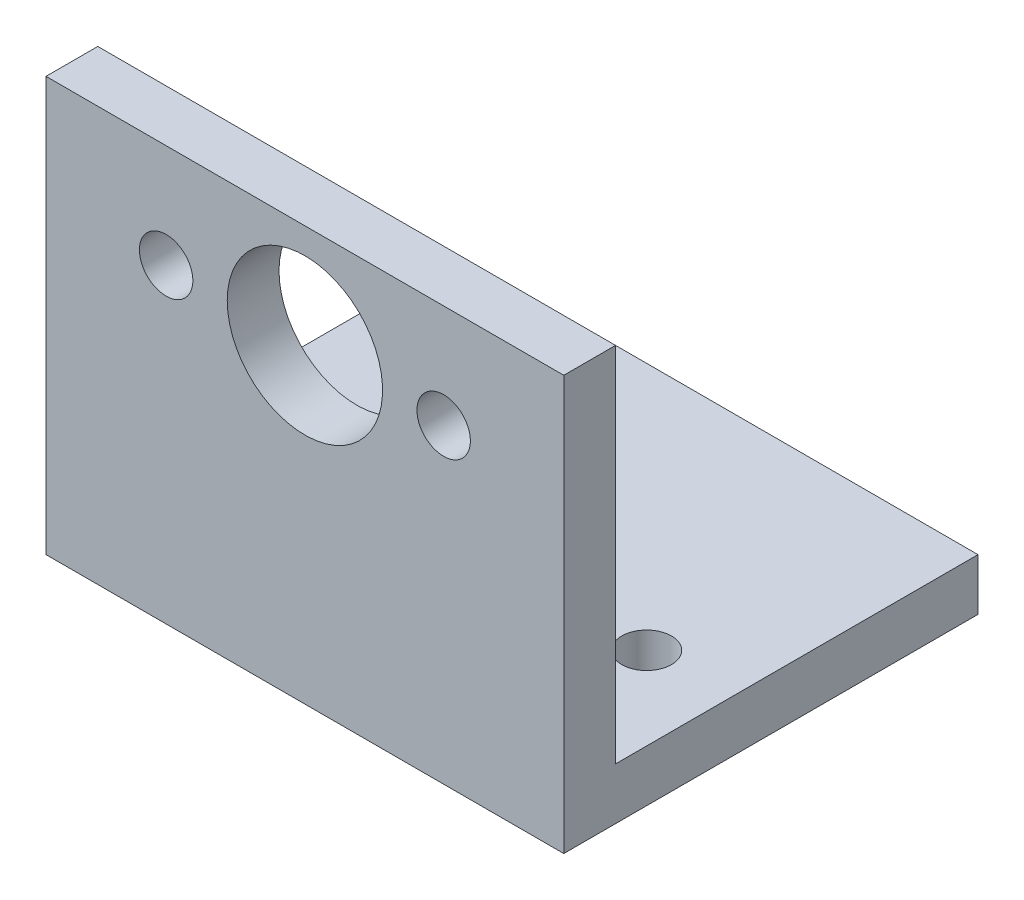
SolidWorks part; units mm, degrees
ref_plane "Front Plane" through (0, 0, 0) normal (0, 0, 1) x (1, 0, 0)
ref_plane "Top Plane" through (0, 0, 0) normal (0, 1, 0) x (1, 0, 0)
ref_plane "Right Plane" through (0, 0, 0) normal (1, 0, 0) x (0, 0, -1)
sketch "Sketch2" plane through (0, 0, 0) normal (1, 0, 0) x (0, 0, -1)
  line L0 (0, 0) -> (25.4, 0)
  line L1 (25.4, 0) -> (25.4, 3.175)
  line L2 (25.4, 3.175) -> (3.175, 3.175)
  line L3 (3.175, 3.175) -> (3.175, 25.4)
  line L4 (3.175, 25.4) -> (0, 25.4)
  line L5 (0, 25.4) -> (0, 0)
  dimension "D1" = 3.175
  dimension "D2" = 3.175
  dimension "D3" = 25.4
  dimension "D4" = 25.4
extrude "Boss-Extrude1" add sketch "Sketch2" along normal blind 31.75
sketch "Sketch3" plane through (0, 0, -3.175) normal (0, 0, -1) x (-1, 0, 0)
  line L1 (0, 3.175) -> (0, 25.4) construction
  line L2 (-31.75, 0) -> (0, 0) construction
  circle A0 centre (-15.875, 19.05) radius 4.7625
  circle A1 centre (-7.366, 19.05) radius 1.6383
  circle A2 centre (-24.384, 19.05) radius 1.6383
  dimension "D1" = 8.509
  dimension "D2" = 8.509
  dimension "D3" = 3.2766
  dimension "D4" = 3.2766
  dimension "D6" = 9.525
  dimension "D5" = 19.05
  dimension "D7" = 15.875
extrude "Cut-Extrude1" cut sketch "Sketch3" against normal through all
sketch "Sketch4" plane through (0, 3.175, 0) normal (0, 1, 0) x (1, 0, 0)
  line L0 (0, 25.4) -> (0, 3.175) construction
  line L1 (31.75, 25.4) -> (31.75, 3.175) construction
  line L2 (31.75, 25.4) -> (0, 25.4) construction
  circle A1 centre (5.08, 21.59) radius 1.524
  circle A2 centre (26.67, 10.16) radius 1.524
  dimension "D1" = 5.08
  dimension "D3" = 5.08
  dimension "D5" = 3.81
  dimension "D6" = 15.24
extrude "Cut-Extrude2" cut sketch "Sketch4" against normal through all
